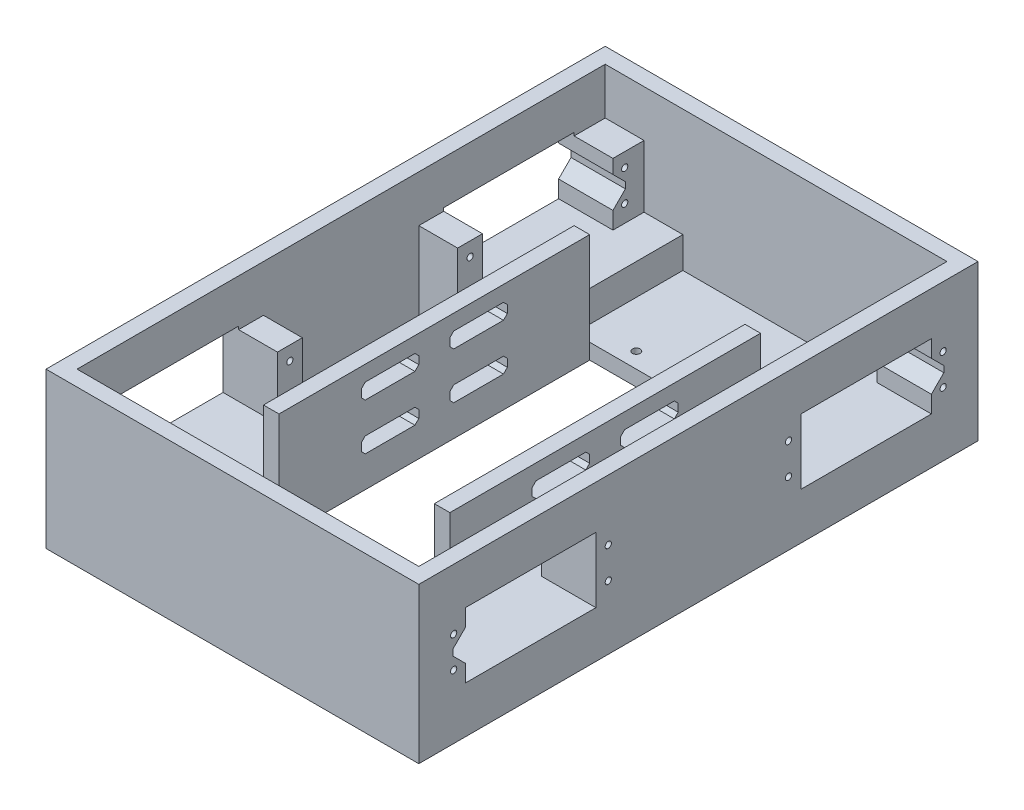
SolidWorks part; units mm, degrees
ref_plane "Front Plane" through (0, 0, 0) normal (0, 0, 1) x (1, 0, 0)
ref_plane "Top Plane" through (0, 0, 0) normal (0, 1, 0) x (1, 0, 0)
ref_plane "Right Plane" through (0, 0, 0) normal (1, 0, 0) x (0, 0, -1)
sketch "Sketch1" plane through (0, 0, 0) normal (0, 1, 0) x (1, 0, 0)
  line L1 (-60, 0) -> (60, 0)
  line L2 (-60, 0) -> (-60, 180)
  line L3 (-60, 180) -> (60, 180)
  line L4 (60, 0) -> (60, 180)
  point P5 (0, 0)
  dimension "D1" = 180
  dimension "D2" = 120
extrude "Boss-Extrude1" add sketch "Sketch1" along normal blind 50
shell "Shell1" thickness 5
sketch "Sketch2" plane through (0, 5, 0) normal (0, 1, 0) x (1, 0, 0)
  line L0 (0, 180) -> (0, 0) construction
  line L1 (60, 180) -> (-60, 180) construction
  line L2 (-60, 0) -> (60, 0) construction
  line L3 (-60, 90) -> (60, 90) construction
  line L4 (-60, 180) -> (-60, 0) construction
  line L5 (60, 0) -> (60, 180) construction
  line L7 (-25, 40) -> (-30, 40)
  line L8 (-25, 40) -> (-25, 140)
  line L9 (-25, 140) -> (-30, 140)
  line L10 (-30, 40) -> (-30, 140)
  line L11 (25, 140) -> (30, 140)
  line L12 (30, 40) -> (30, 140)
  line L13 (25, 40) -> (30, 40)
  line L14 (25, 40) -> (25, 140)
  point P16 (-25, 90)
  dimension "D1" = 100
  dimension "D2" = 5
  dimension "D3" = 25
extrude "Boss-Extrude2" add sketch "Sketch2" along normal blind 30
ref_plane "Plane1" through (0, 0, -90) normal (0, 0, -1) x (-1, 0, 0)
sketch "Sketch3" plane through (0, 5, 0) normal (0, 1, 0) x (1, 0, 0)
  line L1 (-55, 5) -> (-30, 5)
  line L2 (-55, 5) -> (-55, 65)
  line L3 (-55, 65) -> (-30, 65)
  line L4 (-30, 5) -> (-30, 65)
  dimension "D1" = 60
  dimension "D2" = 25
extrude "Boss-Extrude3" add sketch "Sketch3" along normal blind 30
sketch "Sketch4" plane through (-60, 0, 0) normal (-1, 0, 0) x (0, 0, 1)
  line L0 (-180, 0) -> (0, 0) construction
  line L1 (-57, 15) -> (-15, 15)
  line L2 (-57, 15) -> (-57, 36)
  line L3 (-57, 36) -> (-15, 36)
  line L4 (-15, 15) -> (-15, 20.5)
  line L5 (0, 50) -> (0, 0) construction
  line L6 (-15, 30.5) -> (-11, 26.5)
  line L7 (-11, 26.5) -> (-11, 24.5)
  line L8 (-11, 24.5) -> (-15, 20.5)
  line L9 (-15, 30.5) -> (-15, 36)
  circle A0 centre (-61, 30.5) radius 1
  circle A1 centre (-61, 20.5) radius 1
  circle A2 centre (-11.2208, 30.5) radius 1
  circle A3 centre (-11.2208, 20.5) radius 1
  point P16 (-11, 25.5)
  dimension "D5" = 2
  dimension "D1" = 42
  dimension "D2" = 21
  dimension "D3" = 15
  dimension "D4" = 15
  dimension "D6" = 10
  dimension "D7" = 5.5
  dimension "D8" = 4
  dimension "D9" = 4
  dimension "D10" = 135
  dimension "D11" = 10
  dimension "D12" = 10.5
  dimension "D13" = 135
extrude "Cut-Extrude1" cut sketch "Sketch4" against normal up to surface (30 mm away) up to face at (-30, 20, -102.5)
sketch "Sketch5" plane through (0, 35, 0) normal (0, 1, 0) x (1, 0, 0)
  line L0 (-30, 65) -> (-55, 65) construction
  line L1 (-42.5, 65) -> (-30, 65)
  line L2 (-42.5, 65) -> (-42.5, 5)
  line L3 (-42.5, 5) -> (-30, 5)
  line L4 (-30, 65) -> (-30, 5)
  line L5 (-55, 5) -> (-30, 5) construction
  dimension "D1" = 12.5
extrude "Cut-Extrude2" cut sketch "Sketch5" against normal blind 20
sketch "Sketch7" plane through (-25, 0, 0) normal (1, 0, 0) x (0, 0, -1)
  line L0 (66.5, 28.75) -> (67.75, 30)
  line L1 (67.75, 30) -> (83.75, 30)
  line L2 (83.75, 30) -> (85, 28.75)
  line L3 (85, 28.75) -> (85, 26.25)
  line L4 (85, 26.25) -> (83.75, 25)
  line L5 (83.75, 25) -> (67.75, 25)
  line L6 (67.75, 25) -> (66.5, 26.25)
  line L7 (66.5, 26.25) -> (66.5, 28.75)
  line L9 (40, 35) -> (140, 35) construction
  line L10 (66.5, 13.75) -> (67.75, 15)
  line L11 (67.75, 15) -> (83.75, 15)
  line L12 (83.75, 15) -> (85, 13.75)
  line L13 (85, 13.75) -> (85, 11.25)
  line L14 (85, 11.25) -> (83.75, 10)
  line L15 (83.75, 10) -> (67.75, 10)
  line L16 (67.75, 10) -> (66.5, 11.25)
  line L17 (66.5, 11.25) -> (66.5, 13.75)
  line L18 (90, -27.5) -> (90, 27.5) construction
  dimension "D1" = 16
  dimension "D2" = 2.5
  dimension "D3" = 5
  dimension "D4" = 135
  dimension "D5" = 5
  dimension "D6" = 16
  dimension "D7" = 2.5
  dimension "D8" = 5
  dimension "D9" = 135
  dimension "D10" = 20
  dimension "D11" = 5
extrude "Cut-Extrude4" cut sketch "Sketch7" against normal blind 10
sketch "Sketch6" plane through (0, 5, 0) normal (0, 1, 0) x (1, 0, 0)
  line L0 (0, -27.5) -> (0, 27.5) construction
  line L1 (-25, 140) -> (25, 140)
  line L2 (-25, 140) -> (-25, 40)
  line L3 (-25, 40) -> (25, 40)
  line L4 (25, 140) -> (25, 40)
  line L5 (27.5, 90) -> (-27.5, 90) construction
  circle A0 centre (-15, 145) radius 1.25
  circle A1 centre (15, 145) radius 1.25
  circle A2 centre (15, 35) radius 1.25
  circle A3 centre (-15, 35) radius 1.25
  point P8 (0, 140)
  dimension "D1" = 2.5
  dimension "D2" = 5
  dimension "D3" = 15
extrude "Cut-Extrude3" cut sketch "Sketch6" against normal blind 10
mirror "Mirror1" about plane through (0, 0, 0) normal (1, 0, 0) of "Cut-Extrude2", "Cut-Extrude1", "Boss-Extrude3"
mirror "Mirror3" about plane through (0, 0, 0) normal (1, 0, 0) of "Cut-Extrude4"
mirror "Mirror2" about plane through (0, 0, -90) normal (0, 0, -1) of "Mirror3", "Mirror1", "Boss-Extrude3", "Cut-Extrude1", "Cut-Extrude2", "Cut-Extrude4"
